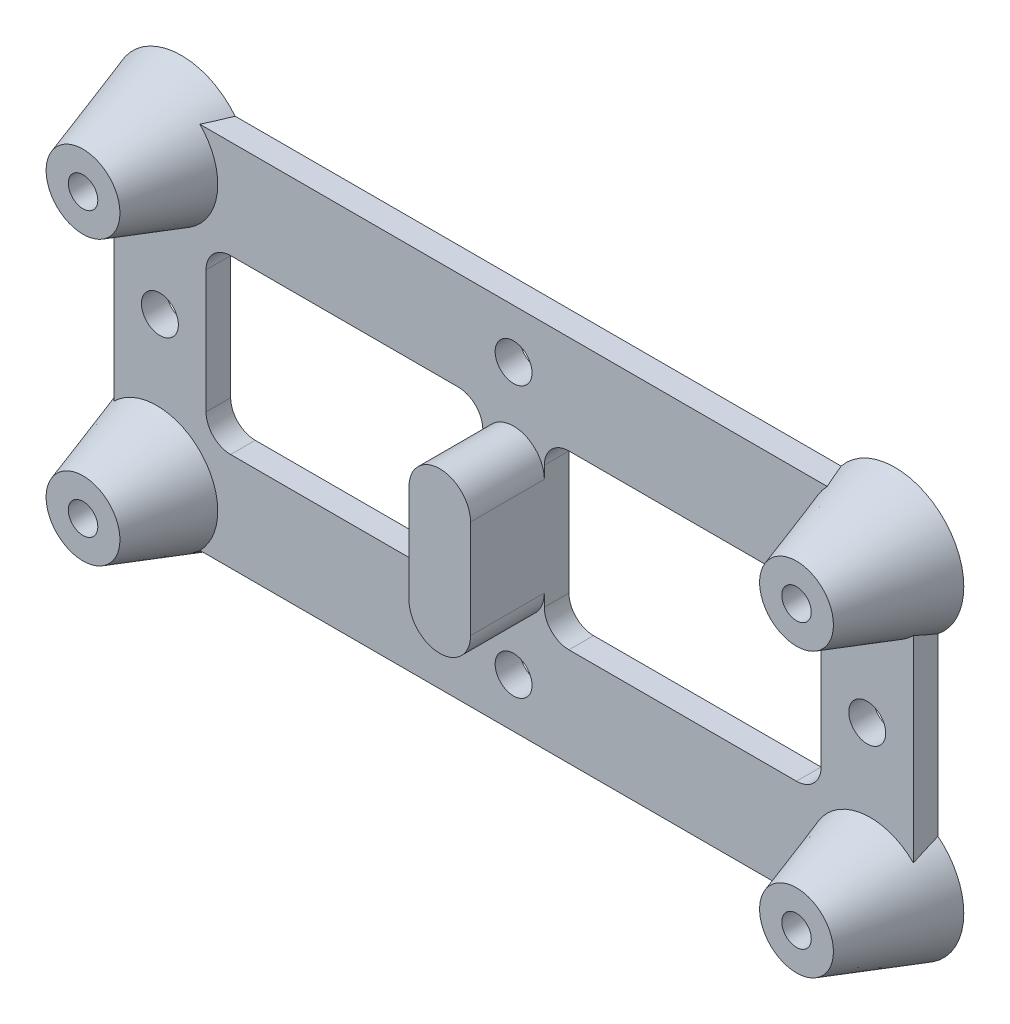
SolidWorks part; units mm, degrees
ref_plane "Plan de face" through (0, 0, 0) normal (0, 0, 1) x (1, 0, 0)
ref_plane "Plan de dessus" through (0, 0, 0) normal (0, 1, 0) x (1, 0, 0)
ref_plane "Plan de droite" through (0, 0, 0) normal (1, 0, 0) x (0, 0, -1)
sketch "Esquisse1" plane through (0, 0, 0) normal (0, 0, 1) x (1, 0, 0)
  line L1 (-32.5, -15) -> (32.5, -15)
  line L2 (-32.5, -15) -> (-32.5, 15)
  line L3 (-32.5, 15) -> (32.5, 15)
  line L4 (32.5, -15) -> (32.5, 15)
  line L5 (-32.5, -15) -> (32.5, 15) construction
  line L6 (-32.5, 15) -> (32.5, -15) construction
  point P0 (0, 0)
  dimension "D1" = 65
  dimension "D2" = 30
extrude "Boss.-Extru.1" add sketch "Esquisse1" along normal blind 2
ref_plane "Plan1" through (0, 0, 8) normal (0, 0, 1) x (1, 0, 0)
sketch "Esquisse2" plane through (0, 0, 8) normal (0, 0, 1) x (1, 0, 0)
  line L1 (-32.5, 15) -> (32.5, 15) construction
  line L2 (-32.5, 15) -> (-32.5, -15) construction
  line L3 (-32.5, -15) -> (32.5, -15) construction
  line L4 (32.5, 15) -> (32.5, -15) construction
  line L5 (29, -11.5) -> (-29, -11.5) construction
  line L6 (29, -11.5) -> (29, 11.5) construction
  line L7 (29, 11.5) -> (-29, 11.5) construction
  line L8 (-29, -11.5) -> (-29, 11.5) construction
  line L9 (29, -11.5) -> (-29, 11.5) construction
  line L10 (29, 11.5) -> (-29, -11.5) construction
  circle A0 centre (-29, 11.5) radius 3
  circle A1 centre (29, 11.5) radius 3
  circle A2 centre (29, -11.5) radius 3
  circle A3 centre (-29, -11.5) radius 3
  point P14 (0, 0)
  dimension "D1" = 6
  dimension "D2" = 3.5
  dimension "D3" = 3.5
extrude "Boss.-Extru.2" add sketch "Esquisse2" against normal up to surface (8 mm away) draft 18
sketch "Esquisse3" plane through (0, 0, 8) normal (0, 0, 1) x (1, 0, 0)
  circle A0 centre (-29, 11.5) radius 1.75
  circle A1 centre (29, 11.5) radius 1.75
  circle A2 centre (29, -11.5) radius 1.75
  circle A3 centre (-29, -11.5) radius 1.75
  dimension "D1" = 3.5
extrude "Enlèv. mat.-Extru.1" [suppressed] cut sketch "Esquisse3" against normal up to next
sketch "Esquisse4" plane through (0, 0, 2) normal (0, 0, 1) x (1, 0, 0)
  line L0 (-32.5, 0) -> (0, 0) construction
  line L5 (25, 7) -> (2.5, 7)
  line L6 (-25, -7) -> (-2.5, -7)
  line L9 (0, 15) -> (0, -15) construction
  line L10 (25.5003, 15) -> (-25.5003, 15) construction
  line L11 (-25.5003, -15) -> (25.5003, -15) construction
  line L12 (-32.5, 8.0003) -> (-32.5, -8.0003) construction
  line L13 (-25, -7) -> (-25, 7)
  line L14 (-25, 7) -> (-2.5, 7)
  line L15 (-2.5, -7) -> (-2.5, 7)
  line L16 (-25, -7) -> (-2.5, 7) construction
  line L17 (-25, 7) -> (-2.5, -7) construction
  line L18 (2.5, -7) -> (2.5, 7)
  line L19 (25, -7) -> (2.5, -7)
  line L20 (25, -7) -> (25, 7)
  point P0 (-16.25, 0)
  point P1 (-13.75, 0)
  point P9 (-16.25, 0)
  dimension "D1" = 22.5
  dimension "D2" = 14
  dimension "D3" = 7.5
extrude "Enlèv. mat.-Extru.2" cut sketch "Esquisse4" against normal up to next
sketch "Esquisse5" plane through (0, 0, 2) normal (0, 0, 1) x (1, 0, 0)
  line L0 (-2.5, 7) -> (2.5, 7) construction
  line L1 (0, 7) -> (0, 15) construction
  line L2 (25.5003, 15) -> (-25.5003, 15) construction
  line L3 (-2.5, -7) -> (2.5, -7) construction
  line L4 (-25, -7) -> (-2.5, -7) construction
  line L5 (2.5, -7) -> (25, -7) construction
  line L6 (0, -7) -> (0, -15) construction
  line L7 (-25.5003, -15) -> (25.5003, -15) construction
  line L8 (-25, 7) -> (-25, -7) construction
  line L9 (-25, 0) -> (-32.5, 0) construction
  line L10 (-32.5, 8.0003) -> (-32.5, -8.0003) construction
  line L11 (25, 7) -> (25, -7) construction
  line L12 (25, 0) -> (32.5, 0) construction
  line L13 (32.5, -8.0003) -> (32.5, 8.0003) construction
  circle A0 centre (-28.75, 0) radius 1.5
  circle A1 centre (0, 11) radius 1.5
  circle A2 centre (0, -11) radius 1.5
  circle A3 centre (28.75, 0) radius 1.5
  point P17 (0, 11)
  point P28 (0, -11)
  point P37 (-28.75, 0)
  point P46 (28.75, 0)
  dimension "D1" = 3
extrude "Enlèv. mat.-Extru.3" cut sketch "Esquisse5" against normal up to next
fillet "Congé1" radius 2 8 edges at (2.5, -7, 1) (2.5, 7, 1) (25, 7, 1) (25, -7, 1) (-2.5, -7, 1) (-25, -7, 1) (-2.5, 7, 1) (-25, 7, 1)
sketch "Esquisse6" plane through (0, 0, 8) normal (0, 0, 1) x (1, 0, 0)
  line L0 (0, -4) -> (0, 4) construction
  line L5 (-2.5, -4) -> (-2.5, 4)
  line L6 (2.5, -4) -> (2.5, 4)
  line L7 (-2.5, -5) -> (-2.5, 5) construction
  arc A0 (-2.5, -4) -> (2.5, -4) centre (0, -4) ccw
  arc A1 (2.5, 4) -> (-2.5, 4) centre (0, 4) ccw
  point P2 (0, 0)
  dimension "D1" = 8
extrude "Boss.-Extru.3" add sketch "Esquisse6" against normal up to next
sketch "Esquisse7" plane through (0, 0, 8) normal (0, 0, 1) x (1, 0, 0)
  circle A0 centre (-29, 11.5) radius 1.2
  circle A1 centre (29, 11.5) radius 1.2
  circle A2 centre (29, -11.5) radius 1.2
  circle A3 centre (-29, -11.5) radius 1.2
  dimension "D1" = 2.4
extrude "Enlèv. mat.-Extru.4" cut sketch "Esquisse7" against normal up to next
